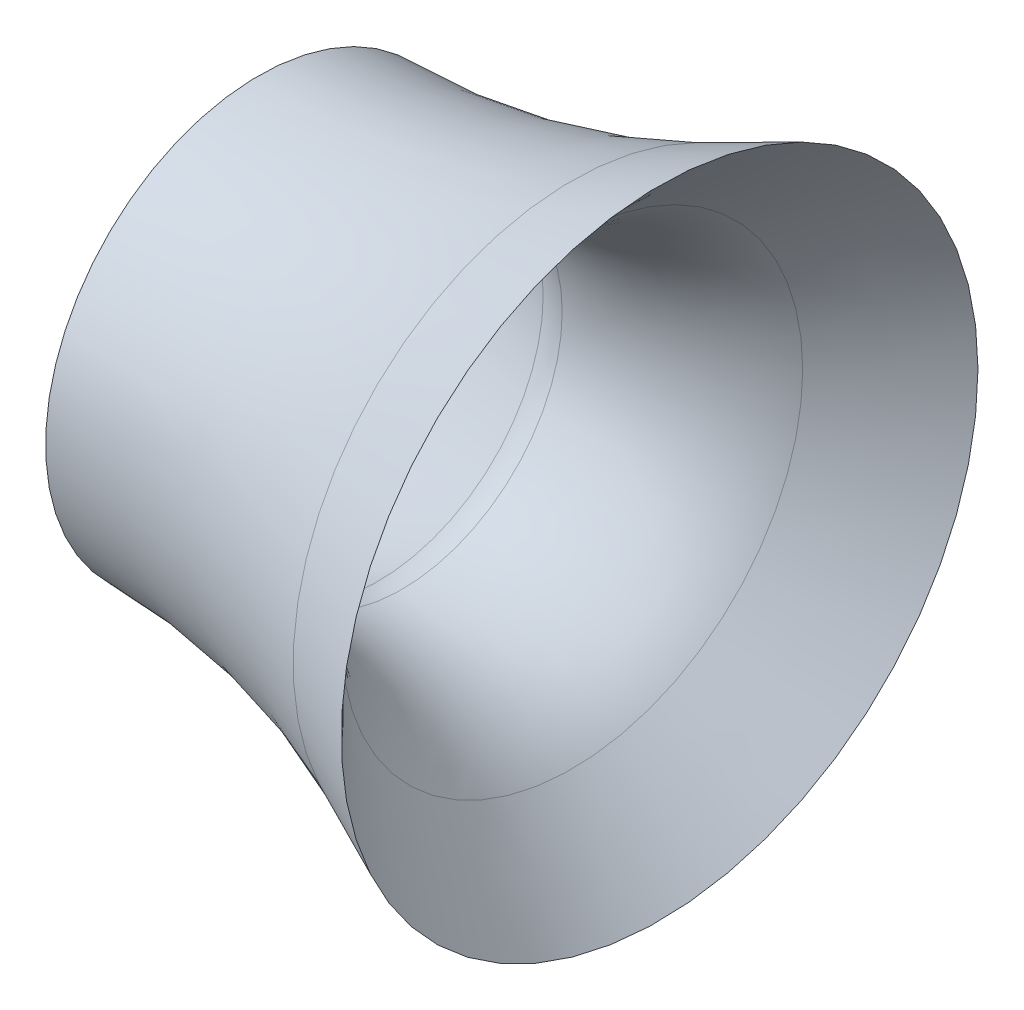
SolidWorks part; units mm, degrees
material "C (Graphite)"
ref_plane "Front Plane" through (0, 0, 0) normal (0, 0, 1) x (1, 0, 0)
ref_plane "Top Plane" through (0, 0, 0) normal (0, 1, 0) x (1, 0, 0)
ref_plane "Right Plane" through (0, 0, 0) normal (1, 0, 0) x (0, 0, -1)
sketch "Sketch1" plane through (0, 0, 0) normal (0, 0, 1) x (1, 0, 0)
  line L0 (189.133, 27.386) -> (28.9492, 27.386)
  line L1 (21.8782, 24.4571) -> (13.5417, 16.1206)
  line L3 (0, 0) -> (-234.9488, 0) construction
  line L5 (16.2213, 30.1139) -> (-13.9816, 25.4377)
  line L6 (-8.3377, 14.8856) -> (19.6623, 22.2412) construction
  line L8 (189.133, 35.386) -> (28.9492, 35.386)
  line L12 (16.2213, 30.1139) -> (7.8848, 21.7775)
  line L13 (189.133, 27.386) -> (189.133, 35.386)
  line L14 (-40.127, 24.64) -> (-38.315, 32.4321)
  line L17 (-8.3377, 14.8856) -> (-11.456, 14.8856) construction
  line L18 (19.6623, 22.2412) -> (22.2041, 23.4265) construction
  line L19 (13.5417, 16.1206) -> (13.5417, 19.4725) construction
  arc A0 (28.9492, 27.386) -> (21.8782, 24.4571) centre (28.9492, 17.386) ccw
  arc A4 (28.9492, 35.386) -> (16.2213, 30.1139) centre (28.9492, 17.386) ccw
  arc A7 (2.3482, 19.2268) -> (2.3482, 19.2268) centre (2.3482, 19.2268) cw
  arc A8 (7.8848, 21.7775) -> (2.3482, 19.2268) centre (1.6623, 28) cw construction
  arc A9 (2.3482, 19.2268) -> (7.8848, 21.7775) centre (1.6623, 28) ccw
  arc A10 (0.1069, 11.2722) -> (0, 11.5361) centre (3.1693, 12.6659) cw construction
  arc A11 (13.5417, 16.1206) -> (0.1069, 11.2722) centre (1.6623, 28) cw construction
  arc A12 (13.5417, 16.1206) -> (1.6623, 11.2) centre (1.6623, 28) cw
  arc A13 (1.6623, 11.2) -> (0, 11.5361) centre (1.6623, 15.4784) cw
  arc A14 (-8.3377, 14.8856) -> (13.5417, 19.4725) centre (-8.3377, 69.3611) ccw
  arc A15 (19.6623, 22.2412) -> (13.5417, 19.4725) centre (-103.6238, 286.629) cw
  spline S0 degree 2 poles (0, 11.5361) (-19.9483, 19.9476) (-40.127, 24.64) knots 0 0 0 1 1 1 construction
  spline S1 degree 1 poles (2.3482, 19.2268) (-38.315, 32.4321) knots 0 0 1 1 construction
  spline S2 degree 2 poles (0, 11.5361) (-19.9483, 19.9476) (-40.127, 24.64) knots 0 0 0 1 1 1
  spline S3 degree 2 poles (2.3482, 19.2268) (0.3135, 20.0775) (-5.8003, 22.5182) (-13.9784, 25.475) (-28.1602, 30.0701) (-38.315, 32.4321) knots 0.018494 0.018494 0.018494 0.117488 0.315475 0.513463 1 1 1
  dimension "D1" = 10
  dimension "D4" = 16.8
  dimension "D5" = 4.2784
  dimension "D14" = 27.386
  dimension "D16" = 167.2548
  dimension "D2" = 11.2
  dimension "D6" = 45
  dimension "D7" = 24.64
  dimension "D8" = 18
  dimension "D9" = 10
  dimension "D10" = 20
  dimension "D3" = 8
revolve "Revolve1" add sketch "Sketch1" angle 360 about L3
equation "\"theta_t\"= 36.9009 - ( 426.271 / ( \"Aet\" + 7.00037 ) ) + ( 10026.8 / ( \"Aet\" + 7.00037 ) ^ 2 ) - ( 175410 / ( \"Aet\" + 7.00037 ) ^ 3 ) + ( ( 1.6742 * ( 10 ^ 6 ) ) / ( \"Aet\" + 7.00037 ) ^ 4 ) - ( ( 6.7643 * ( 10 ^ 6 ) ) / ( \"Aet\" + 7.00037 ) ^ 5 )"
equation "\"rt\"= 11.2"
equation "\"re\"= sqr ( \"rt\" ^ 2 * \"Aet\" )"
equation "\"Aet\"= 4.84"
equation "\"L\"= 0.8 * ( ( \"re\" / tan ( 15 ) ) - ( \"rt\" / tan ( 15 ) ) )"
equation "\"lc\"= ( \"l*\" / \"cr\" )"
equation "\"b\"= tan ( \"theta_t\" )"
equation "\"a\"= ( \"re\" - \"b\" * \"L\" - \"c\" ) / \"L\" ^ 2"
equation "\"c\"= \"rt\" * ( 1.382 - 0.382 * cos ( \"theta_t\" ) )"
equation "\"cr\"= 5.9789"
equation "\"rc\"= sqr ( \"cr\" * ( \"rt\" ^ 2 ) )"
equation "\"D14@Sketch1\"=\"rc\""
equation "\"l*\"= 1000"
equation "\"D16@Sketch1\"=\"lc\""
equation "\"th\"= 8"
equation "\"theta_cr\"= 45deg"
equation "\"theta_e\"= 5.48 + ( 134.316 / ( \"Aet\" + 1.49269 ) ) - ( 1742.02 / ( \"Aet\" + 1.49269 ) ^ 2 ) + ( 13091 / ( \"Aet\" + 1.49269 ) ^ 3 ) - ( 41929.9 / ( \"Aet\" + 1.49269 ) ^ 4 ) + ( 44445.1 / ( \"Aet\" + 1.49269 ) ^ 5 )"
equation "\"Nx\"= 0"
equation "\"Ny\"= \"c\""
equation "\"Qx\"= ( \"re\" - ( tan ( \"theta_e\" ) * \"L\" ) - \"c\" ) / ( tan ( \"theta_t\" ) - tan ( \"theta_e\" ) )"
equation "\"Qy\"= tan ( \"theta_t\" ) * \"Qx\" + \"c\""
equation "\"Ex\"= \"L\""
equation "\"Ey\"= \"re\""
equation "\"D3@Sketch1\"=\"th\""
equation "\"D2@Sketch1\"=\"rt\""
equation "\"D4@Sketch1\"=\"rt\"*1.5"
equation "\"D5@Sketch1\"=\"rt\"*0.382"
equation "\"D6@Sketch1\"=\"theta_cr\""
equation "\"D7@Sketch1\"=\"re\""
